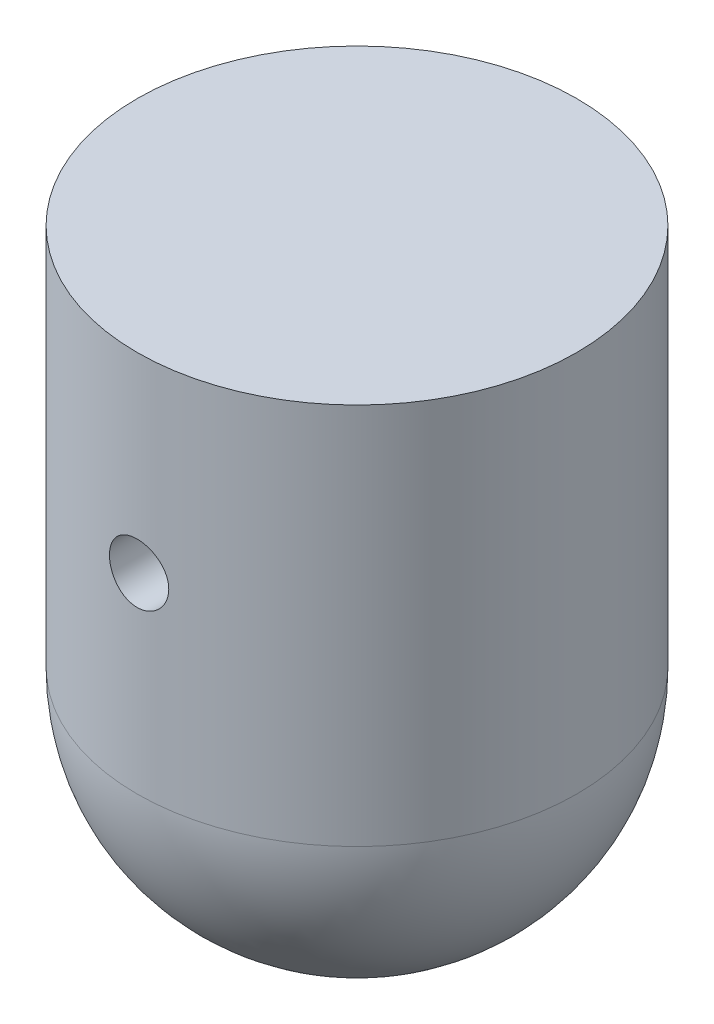
SolidWorks part; units mm, degrees
material "PLA"
ref_plane "Front Plane" through (0, 0, 0) normal (0, 0, 1) x (1, 0, 0)
ref_plane "Top Plane" through (0, 0, 0) normal (0, 1, 0) x (1, 0, 0)
ref_plane "Right Plane" through (0, 0, 0) normal (1, 0, 0) x (0, 0, -1)
sketch "Sketch1" plane through (0, 0, 0) normal (0, 1, 0) x (1, 0, 0)
  line L0 (0, -44.7868) -> (0, 44.7868) construction
  line L1 (0, 11.5) -> (0, -11.5)
  line L2 (0, 22.0214) -> (0, -22.0214) construction
  arc A0 (0, 11.5) -> (0, -11.5) centre (0, 0) ccw
  dimension "D1" = 11.5
revolve "Revolve1" add sketch "Sketch1" angle 180 about L2
sketch "Sketch4" plane through (0, 0, 0) normal (0, 1, 0) x (1, 0, 0)
  circle A0 centre (0, 0) radius 11.5
  dimension "D1" = 23
extrude "Boss-Extrude1" add sketch "Sketch4" along normal blind 20
sketch "Sketch5" plane through (0, 0, 0) normal (0, 0, 1) x (1, 0, 0)
  line L0 (0, -44.7868) -> (0, 44.7868) construction
  line L1 (11.5, 20) -> (-11.5, 20) construction
  circle A0 centre (0, 10) radius 1.55
  dimension "D1" = 3.1
  dimension "D2" = 10
extrude "Cut-Extrude1" cut sketch "Sketch5" against normal mid plane 23
equation "\"TubeRad\" = 11.5"
equation "\"D1@Sketch1\"=\"TubeRad\""
equation "\"D1@Sketch4\"=\"TubeRad\"*2"
equation "\"ExtrusionLength\"=20"
equation "\"D1@Boss-Extrude1\"=\"ExtrusionLength\""
equation "\"MountHoleSize\"=3.1"
equation "\"D1@Sketch5\"=\"MountHoleSize\""
equation "\"MountHoleDist\"=10"
equation "\"D2@Sketch5\"=\"MountHoleDist\""
equation "\"D1@Cut-Extrude1\"=\"TubeRad\"*2"
